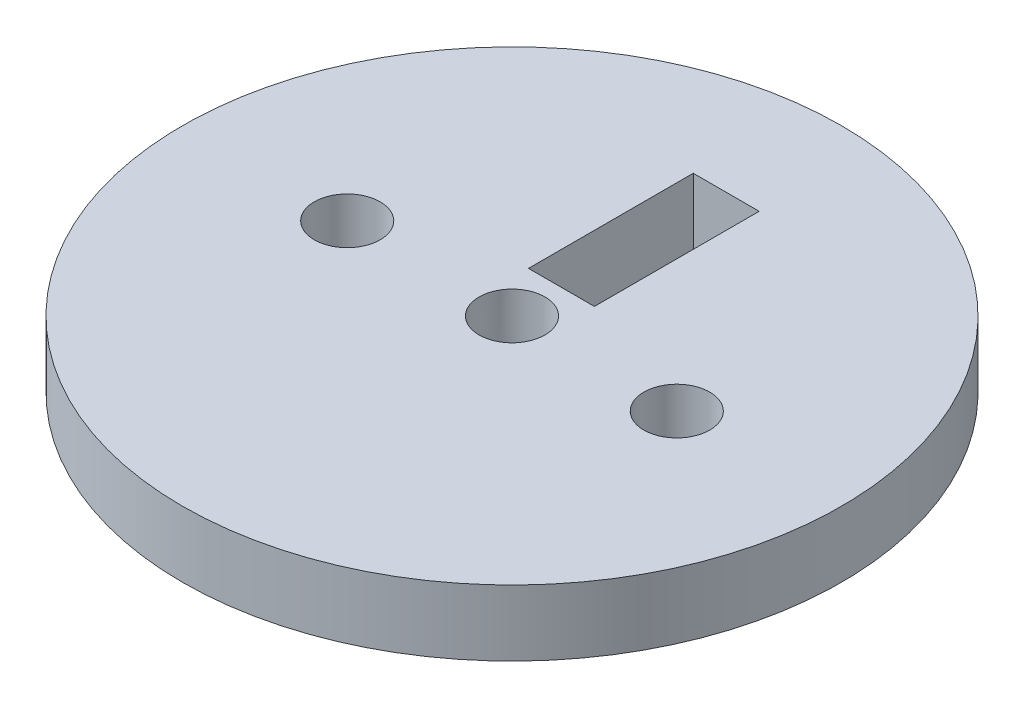
SolidWorks part; units mm, degrees
material "Acrylic (Medium-high impact)"
ref_plane "Front Plane" through (0, 0, 0) normal (0, 0, 1) x (1, 0, 0)
ref_plane "Top Plane" through (0, 0, 0) normal (0, 1, 0) x (1, 0, 0)
ref_plane "Right Plane" through (0, 0, 0) normal (1, 0, 0) x (0, 0, -1)
sketch "Sketch1" plane through (0, 0, 0) normal (0, 1, 0) x (1, 0, 0)
  circle A0 centre (0, 0) radius 10
  dimension "D1" = 20
extrude "Boss-Extrude1" add sketch "Sketch1" along normal blind 2
sketch "Sketch2" plane through (0, 2, 0) normal (0, 1, 0) x (1, 0, 0)
  line L0 (0, -5.6987) -> (0, -8.7477) construction
  line L1 (1, 1.5) -> (-1, 1.5)
  line L2 (1, 1.5) -> (1, 6.5)
  line L3 (1, 6.5) -> (-1, 6.5)
  line L4 (-1, 1.5) -> (-1, 6.5)
  line L5 (1, 1.5) -> (-1, 6.5) construction
  line L6 (1, 6.5) -> (-1, 1.5) construction
  circle A0 centre (0, 0) radius 1
  circle A1 centre (5, 0) radius 1
  circle A3 centre (-5, 0) radius 1
  point P0 (0, 4)
  dimension "D5" = 2
  dimension "D6" = 2
  dimension "D1" = 5
  dimension "D2" = 2
  dimension "D3" = 0
  dimension "D4" = 4
  dimension "D7" = 5
  dimension "D8" = 1.5
extrude "Cut-Extrude1" cut sketch "Sketch2" against normal blind 2
sketch "Sketch3" plane through (0, 0, 0) normal (0, -1, 0) x (1, 0, 0)
  circle A0 centre (0, 0) radius 3.2
  dimension "D1" = 6.4
extrude "Cut-Extrude2" cut sketch "Sketch3" against normal blind 0.2
